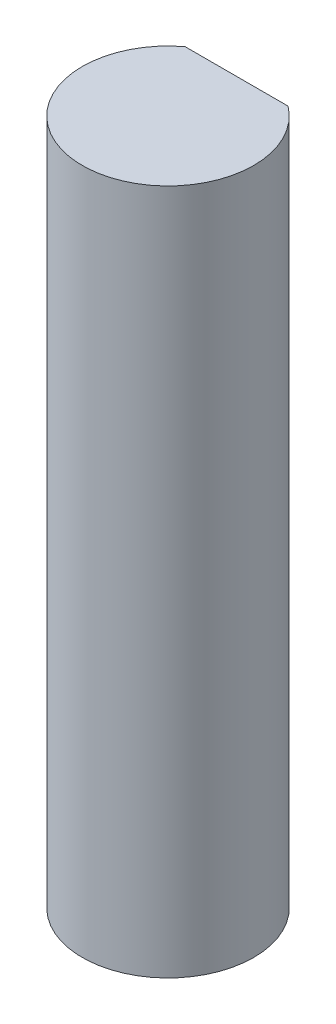
SolidWorks part; units mm, degrees
ref_plane "Front Plane" through (0, 0, 0) normal (0, 0, 1) x (1, 0, 0)
ref_plane "Top Plane" through (0, 0, 0) normal (0, 1, 0) x (1, 0, 0)
ref_plane "Right Plane" through (0, 0, 0) normal (1, 0, 0) x (0, 0, -1)
sketch "Sketch1" plane through (0, 0, 0) normal (0, 1, 0) x (1, 0, 0)
  circle A0 centre (0, 0) radius 3.175
  dimension "D1" = 6.35
extrude "Boss-Extrude1" add sketch "Sketch1" along normal blind 25.4
sketch "Sketch2" plane through (0, 0, 0) normal (0, -1, 0) x (1, 0, 0)
  line L0 (1.905, -2.54) -> (-1.905, -2.54)
  line L1 (0, 0) -> (0, -2.54) construction
  circle A0 centre (0, 0) radius 3.175 construction
  arc A1 (-1.905, -2.54) -> (1.905, -2.54) centre (0, 0) ccw
  dimension "D1" = 5.715
extrude "Cut-Extrude1" cut sketch "Sketch2" against normal through all
